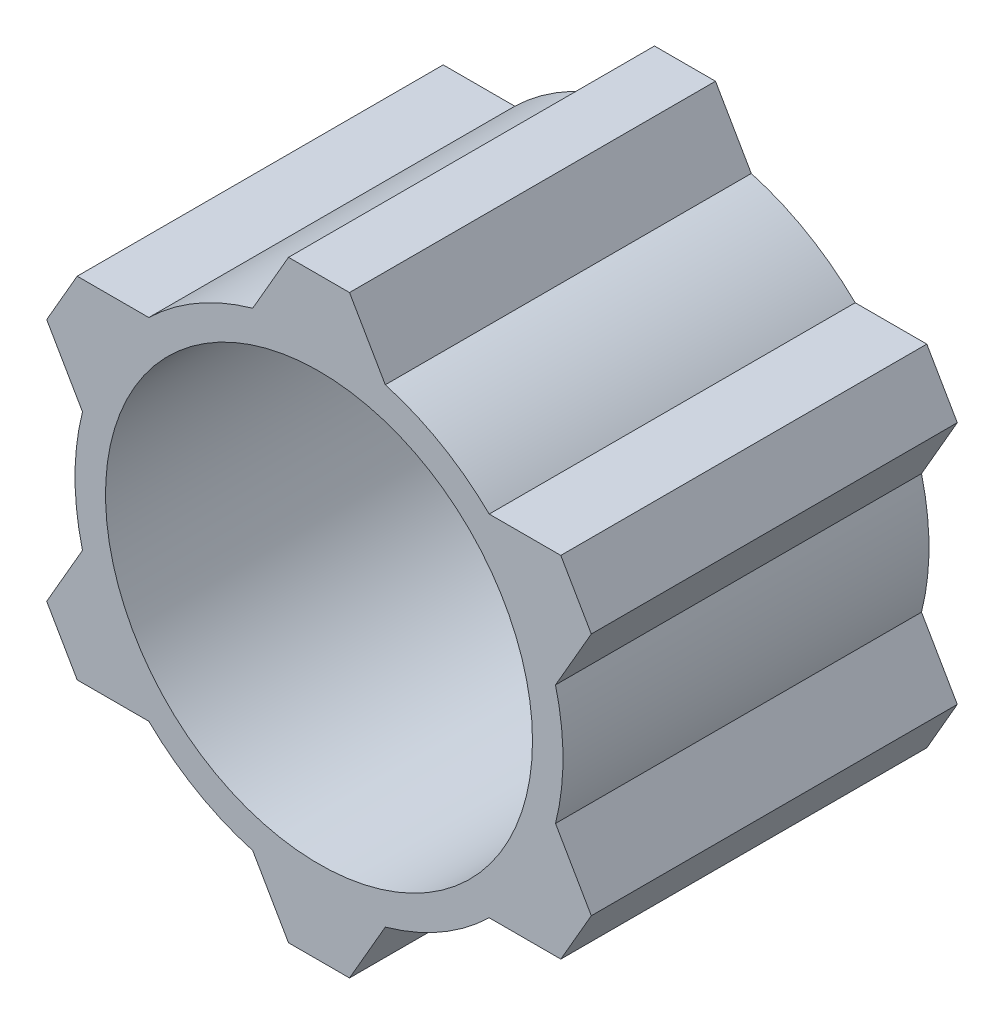
SolidWorks part; units mm, degrees
ref_plane "Front Plane" through (0, 0, 0) normal (0, 0, 1) x (1, 0, 0)
ref_plane "Top Plane" through (0, 0, 0) normal (0, 1, 0) x (1, 0, 0)
ref_plane "Right Plane" through (0, 0, 0) normal (1, 0, 0) x (0, 0, -1)
sketch "Sketch1" plane through (0, 0, 0) normal (0, 0, 1) x (1, 0, 0)
  line L0 (-5, 48.6603) -> (-10, 40)
  line L1 (10, 40) -> (5, 48.6603)
  line L2 (5, 48.6603) -> (-5, 48.6603)
  line L7 (-10, 40) -> (-10.8689, 38.495)
  line L8 (10, 40) -> (10.8689, 38.495)
  line L9 (39.641, 28.6603) -> (29.641, 28.6603)
  line L10 (44.641, 20) -> (39.641, 28.6603)
  line L11 (0, 31.3397) -> (5, 31.3397) [skipped]
  line L12 (9.359, 38.8897) -> (10, 40) [skipped]
  line L13 (-10, 40) -> (-9.359, 38.8897) [skipped]
  line L14 (39.641, 11.3397) -> (44.641, 20)
  line L15 (39.641, 11.3397) -> (38.7721, 9.8348)
  line L16 (29.641, 28.6603) -> (27.9032, 28.6603)
  line L17 (44.641, -20) -> (39.641, -11.3397)
  line L18 (39.641, -28.6603) -> (44.641, -20)
  line L19 (29.641, -28.6603) -> (39.641, -28.6603)
  line L20 (29.641, -28.6603) -> (27.9032, -28.6603)
  line L21 (39.641, -11.3397) -> (38.7721, -9.8348)
  line L22 (5, -48.6603) -> (10, -40)
  line L23 (-5, -48.6603) -> (5, -48.6603)
  line L24 (-10, -40) -> (-5, -48.6603)
  line L25 (-10, -40) -> (-10.8689, -38.495)
  line L26 (10, -40) -> (10.8689, -38.495)
  line L27 (-39.641, -28.6603) -> (-29.641, -28.6603)
  line L28 (-44.641, -20) -> (-39.641, -28.6603)
  line L29 (-39.641, -11.3397) -> (-44.641, -20)
  line L30 (-39.641, -11.3397) -> (-38.7721, -9.8348)
  line L31 (-29.641, -28.6603) -> (-27.9032, -28.6603)
  line L32 (-44.641, 20) -> (-39.641, 11.3397)
  line L33 (-39.641, 28.6603) -> (-44.641, 20)
  line L34 (-29.641, 28.6603) -> (-39.641, 28.6603)
  line L35 (-29.641, 28.6603) -> (-27.9032, 28.6603)
  line L36 (-39.641, 11.3397) -> (-38.7721, 9.8348)
  line L37 (0, 10) -> (0, 32.5) construction
  line L38 (-2.5, 9.6825) -> (-2.5, 34.9106)
  line L39 (2.5, 34.9106) -> (2.5, 9.6825)
  line L40 (7.1353, 7.0063) -> (28.9835, 19.6204)
  line L41 (31.4835, 15.2902) -> (9.6353, 2.6762)
  line L42 (9.6353, -2.6762) -> (31.4835, -15.2902)
  line L43 (28.9835, -19.6204) -> (7.1353, -7.0063)
  line L44 (2.5, -9.6825) -> (2.5, -34.9106)
  line L45 (-2.5, -34.9106) -> (-2.5, -9.6825)
  line L46 (-7.1353, -7.0063) -> (-28.9835, -19.6204)
  line L47 (-31.4835, -15.2902) -> (-9.6353, -2.6762)
  line L48 (-9.6353, 2.6762) -> (-31.4835, 15.2902)
  line L49 (-28.9835, 19.6204) -> (-7.1353, 7.0063)
  line L50 (-5, 48.6603) -> (-10, 40) [skipped]
  arc A0 (-10.8689, 38.495) -> (-27.9032, 28.6603) centre (0, 0) ccw
  arc A1 (-2.5, 34.9106) -> (-28.9835, 19.6204) centre (0, 0) ccw
  circle A2 centre (0, 0) radius 5
  arc A3 (-2.5, 9.6825) -> (-7.1353, 7.0063) centre (0, 0) ccw
  arc A4 (-9.6353, 2.6762) -> (-9.6353, -2.6762) centre (0, 0) ccw
  arc A5 (-7.1353, -7.0063) -> (-2.5, -9.6825) centre (0, 0) ccw
  arc A6 (2.5, -9.6825) -> (7.1353, -7.0063) centre (0, 0) ccw
  arc A7 (9.6353, -2.6762) -> (9.6353, 2.6762) centre (0, 0) ccw
  arc A8 (7.1353, 7.0063) -> (2.5, 9.6825) centre (0, 0) ccw
  arc A9 (-38.7721, 9.8348) -> (-38.7721, -9.8348) centre (0, 0) ccw
  arc A10 (-31.4835, 15.2902) -> (-31.4835, -15.2902) centre (0, 0) ccw
  arc A11 (27.9032, 28.6603) -> (10.8689, 38.495) centre (0, 0) ccw
  arc A12 (28.9835, 19.6204) -> (2.5, 34.9106) centre (0, 0) ccw
  arc A13 (31.4835, -15.2902) -> (31.4835, 15.2902) centre (0, 0) ccw
  arc A14 (38.7721, -9.8348) -> (38.7721, 9.8348) centre (0, 0) ccw
  arc A15 (2.5, -34.9106) -> (28.9835, -19.6204) centre (0, 0) ccw
  arc A16 (10.8689, -38.495) -> (27.9032, -28.6603) centre (0, 0) ccw
  arc A17 (-28.9835, -19.6204) -> (-2.5, -34.9106) centre (0, 0) ccw
  arc A18 (-27.9032, -28.6603) -> (-10.8689, -38.495) centre (0, 0) ccw
  point P51 (0, 0)
  point P78 (0, 0)
  dimension "D1" = 80
  dimension "D2" = 70
  dimension "D3" = 10
  dimension "D4" = 20
  dimension "D5" = 20
  dimension "D7" = 5
  dimension "D6" = 6
  dimension "D8" = 6
extrude "Boss-Extrude1" add sketch "Sketch1" along normal blind 10
sketch "Sketch2" plane through (0, 0, 10) normal (0, 0, 1) x (1, 0, 0)
  line L0 (-38.7721, 9.8348) -> (-44.641, 20)
  line L1 (-44.641, 20) -> (-39.641, 28.6603)
  line L2 (-39.641, 28.6603) -> (-27.9032, 28.6603)
  line L3 (-10.8689, 38.495) -> (-5, 48.6603)
  line L4 (-5, 48.6603) -> (5, 48.6603)
  line L5 (5, 48.6603) -> (10.8689, 38.495)
  line L6 (27.9032, 28.6603) -> (39.641, 28.6603)
  line L7 (39.641, 28.6603) -> (44.641, 20)
  line L8 (44.641, 20) -> (38.7721, 9.8348)
  line L9 (38.7721, -9.8348) -> (44.641, -20)
  line L10 (44.641, -20) -> (39.641, -28.6603)
  line L11 (39.641, -28.6603) -> (27.9032, -28.6603)
  line L12 (10.8689, -38.495) -> (5, -48.6603)
  line L13 (5, -48.6603) -> (-5, -48.6603)
  line L14 (-5, -48.6603) -> (-10.8689, -38.495)
  line L15 (-27.9032, -28.6603) -> (-39.641, -28.6603)
  line L16 (-39.641, -28.6603) -> (-44.641, -20)
  line L17 (-44.641, -20) -> (-38.7721, -9.8348)
  circle A0 centre (0, 0) radius 35
  arc A1 (-38.7721, 9.8348) -> (-38.7721, -9.8348) centre (0, 0) ccw
  arc A2 (-27.9032, -28.6603) -> (-10.8689, -38.495) centre (0, 0) ccw
  arc A3 (10.8689, -38.495) -> (27.9032, -28.6603) centre (0, 0) ccw
  arc A4 (38.7721, -9.8348) -> (38.7721, 9.8348) centre (0, 0) ccw
  arc A5 (27.9032, 28.6603) -> (10.8689, 38.495) centre (0, 0) ccw
  point P34 (0, 0)
  arc M4 (27.9032, 28.6603) -> (10.8689, 38.495) centre (0, 0) ccw
  line M5 (10.8689, 38.495) -> (5, 48.6603)
  line M6 (5, 48.6603) -> (-5, 48.6603)
  line M7 (-5, 48.6603) -> (-10.8689, 38.495)
  arc M8 (-10.8689, 38.495) -> (-27.9032, 28.6603) centre (0, 0) ccw
  line M9 (-27.9032, 28.6603) -> (-39.641, 28.6603)
  line M10 (-39.641, 28.6603) -> (-44.641, 20)
  line M11 (-44.641, 20) -> (-38.7721, 9.8348)
  arc M12 (-38.7721, 9.8348) -> (-38.7721, -9.8348) centre (0, 0) ccw
  line M13 (-38.7721, -9.8348) -> (-44.641, -20)
  line M14 (-44.641, -20) -> (-39.641, -28.6603)
  line M15 (-39.641, -28.6603) -> (-27.9032, -28.6603)
  arc M16 (-27.9032, -28.6603) -> (-10.8689, -38.495) centre (0, 0) ccw
  line M17 (-10.8689, -38.495) -> (-5, -48.6603)
  line M18 (-5, -48.6603) -> (5, -48.6603)
  line M19 (5, -48.6603) -> (10.8689, -38.495)
  arc M20 (10.8689, -38.495) -> (27.9032, -28.6603) centre (0, 0) ccw
  line M21 (27.9032, -28.6603) -> (39.641, -28.6603)
  line M22 (39.641, -28.6603) -> (44.641, -20)
  line M23 (44.641, -20) -> (38.7721, -9.8348)
  arc M24 (38.7721, -9.8348) -> (38.7721, 9.8348) centre (0, 0) ccw
  line M25 (38.7721, 9.8348) -> (44.641, 20)
  line M26 (44.641, 20) -> (39.641, 28.6603)
  line M27 (39.641, 28.6603) -> (27.9032, 28.6603)
  arc M32 (2.5, 34.9106) -> (28.9835, 19.6204) centre (0, 0) cw
  arc M34 (-28.9835, 19.6204) -> (-2.5, 34.9106) centre (0, 0) cw
  arc M40 (31.4835, 15.2902) -> (31.4835, -15.2902) centre (0, 0) cw
  arc M44 (28.9835, -19.6204) -> (2.5, -34.9106) centre (0, 0) cw
  arc M48 (-2.5, -34.9106) -> (-28.9835, -19.6204) centre (0, 0) cw
  arc M52 (-31.4835, -15.2902) -> (-31.4835, 15.2902) centre (0, 0) cw
  dimension "D1" = 6
extrude "Boss-Extrude2" add sketch "Sketch2" along normal blind 50 contours A0 M27 M4 M5 M6 M7 M8 M9 M10 M11 M12 M13 M14 M15 M16 M17 M18 M19 M20 M21 M22 M23 M24 M25 M26 M40 M44 M48 M52 M34 M32
